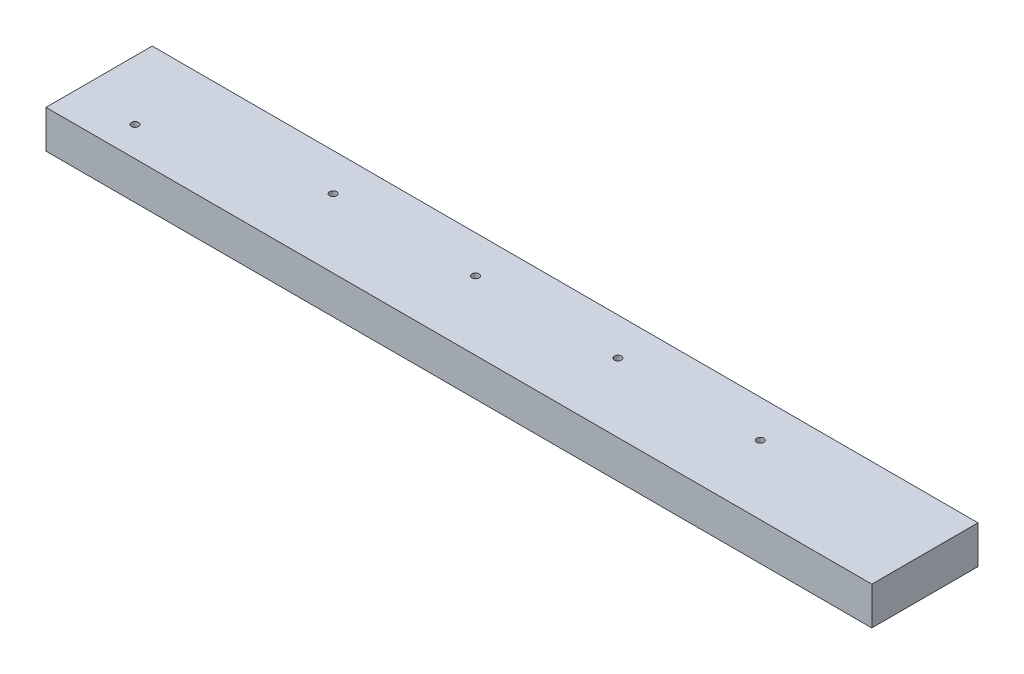
SolidWorks part; units mm, degrees
ref_plane "Front Plane" through (0, 0, 0) normal (0, 0, 1) x (1, 0, 0)
ref_plane "Top Plane" through (0, 0, 0) normal (0, 1, 0) x (1, 0, 0)
ref_plane "Right Plane" through (0, 0, 0) normal (1, 0, 0) x (0, 0, -1)
sketch "Sketch1" plane through (0, 0, 0) normal (0, 1, 0) x (1, 0, 0)
  line L1 (1104.9, 142.0813) -> (-1104.9, 142.0812)
  line L2 (1104.9, 142.0813) -> (1104.9, -142.0812)
  line L3 (1104.9, -142.0812) -> (-1104.9, -142.0813)
  line L4 (-1104.9, 142.0812) -> (-1104.9, -142.0813)
  line L5 (1104.9, 142.0813) -> (-1104.9, -142.0813) construction
  line L6 (1104.9, -142.0812) -> (-1104.9, 142.0812) construction
  point P0 (0, 0)
  dimension "D1" = 2209.8
  dimension "D2" = 284.1625
extrude "Boss-Extrude1" add sketch "Sketch1" along normal mid plane 101.6
sketch "Sketch2" plane through (0, 50.8, 0) normal (0, 1, 0) x (1, 0, 0)
  line L0 (-1104.9, 142.0812) -> (-1104.9, -142.0813) construction
  line L1 (1104.9, 142.0813) -> (-1104.9, 142.0812) construction
  circle A0 centre (-946.15, -62.7062) radius 9.525
  circle A1 centre (-520.7, 42.0688) radius 9.525
  circle A2 centre (-139.7, 42.0688) radius 9.525
  circle A3 centre (241.3, 42.0688) radius 9.525
  circle A4 centre (622.3, 42.0688) radius 9.525
  dimension "D1" = 19.05
  dimension "D4" = 425.45
  dimension "D5" = 100.0125
  dimension "D2" = 158.75
  dimension "D3" = 204.7875
  dimension "D7" = 965.2
  dimension "D6" = 4
extrude "Cut-Extrude1" cut sketch "Sketch2" against normal through all
sketch "Sketch3" plane through (0, -50.8, 0) normal (0, -1, 0) x (1, 0, 0)
  line L0 (1104.9, -142.0813) -> (-1104.9, -142.0812) construction
  line L1 (488.95, -69.0563) -> (574.675, -69.0563)
  line L2 (488.95, -69.0563) -> (488.95, -113.5063)
  line L3 (488.95, -113.5063) -> (574.675, -113.5063)
  line L4 (574.675, -69.0563) -> (574.675, -113.5063)
  line L5 (488.95, -69.0563) -> (574.675, -113.5063) construction
  line L6 (488.95, -113.5063) -> (574.675, -69.0563) construction
  line L7 (1104.9, 142.0812) -> (1104.9, -142.0813) construction
  line L8 (-704.85, -69.0563) -> (-619.125, -69.0563)
  line L9 (-704.85, -69.0563) -> (-704.85, -113.5063)
  line L10 (-704.85, -113.5063) -> (-619.125, -113.5063)
  line L11 (-619.125, -69.0563) -> (-619.125, -113.5063)
  line L12 (-704.85, -69.0563) -> (-619.125, -113.5063) construction
  line L13 (-704.85, -113.5063) -> (-619.125, -69.0563) construction
  circle A0 centre (-946.15, 62.7062) radius 9.525 construction
  point P0 (531.8125, -91.2813)
  point P8 (-661.9875, -91.2813)
  dimension "D1" = 28.575
  dimension "D2" = 44.45
  dimension "D3" = 85.725
  dimension "D4" = 530.225
  dimension "D6" = 1108.075
  dimension "D7" = 131.7625
  dimension "D5" = 2
extrude "Cut-Extrude2" cut sketch "Sketch3" against normal blind 25.4
